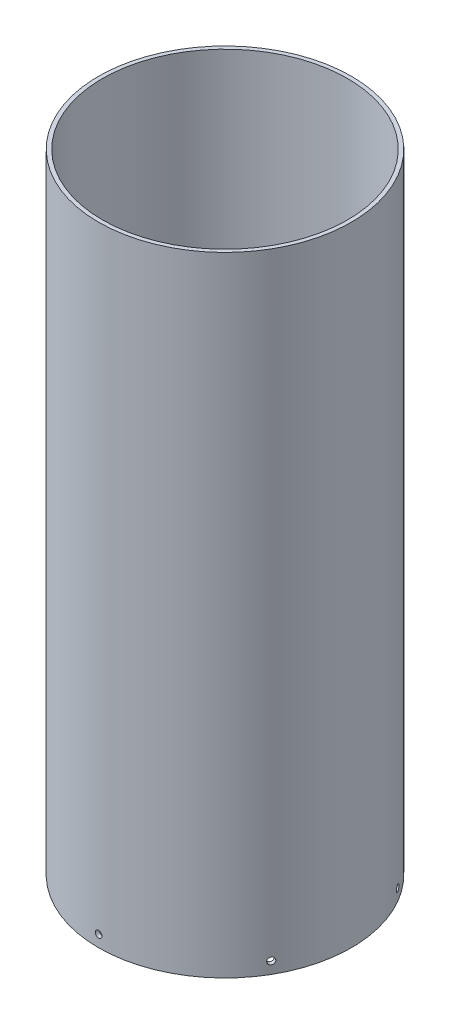
SolidWorks part; units mm, degrees
ref_plane "Front Plane" through (0, 0, 0) normal (0, 0, 1) x (1, 0, 0)
ref_plane "Top Plane" through (0, 0, 0) normal (0, 1, 0) x (1, 0, 0)
ref_plane "Right Plane" through (0, 0, 0) normal (1, 0, 0) x (0, 0, -1)
sketch "Sketch1" plane through (0, 0, 0) normal (0, 1, 0) x (1, 0, 0)
  circle A0 centre (0, 0) radius 51.1048
  circle A1 centre (0, 0) radius 49.53
  dimension "D1" = 102.2096
  dimension "D2" = 99.06
extrude "Boss-Extrude1" add sketch "Sketch1" along normal blind 254
sketch "Sketch2" plane through (0, 0, 0) normal (0, 0, 1) x (1, 0, 0)
  line L0 (0, 0) -> (0, 4.7625)
  line L2 (-51.1048, 0) -> (51.1048, 0) construction
  circle A0 centre (0, 4.7625) radius 1.3526
  dimension "D2" = 2.7051
  dimension "D1" = 4.7625
extrude "Cut-Extrude1" cut sketch "Sketch2" against normal through all
ref_axis "Axis1" through (0, 254, 0) along (0, -1, 0)
pattern_circular "CirPattern1" count 6 over 360 about axis through (0, 254, 0) along (0, -1, 0) of "Cut-Extrude1"
equation "\"Body_Tube_OD\"= 4.024in"
equation "\"Body_Tube_ID\"= 3.90in"
equation "\"D1@Sketch1\"=\"Body_Tube_OD\""
equation "\"D2@Sketch1\"=\"Body_Tube_ID\""
equation "\"Aft_Upper_Tube_Length\" = 10in"
equation "\"D1@Boss-Extrude1\" = \"Aft_Upper_Tube_Length\""
equation "\"AB_Coupling_Section_Length\"= 0.375in"
equation "\"AB_Coupler_Num_Screws\"= 6"
equation "\"AB_Coupling_Screw_Diameter\"= 0.1065in"
equation "\"D1@Sketch2\"=\"AB_Coupling_Section_Length\"/2"
equation "\"D2@Sketch2\"=\"AB_Coupling_Screw_Diameter\""
equation "\"D1@CirPattern1\"=\"AB_Coupler_Num_Screws\""
